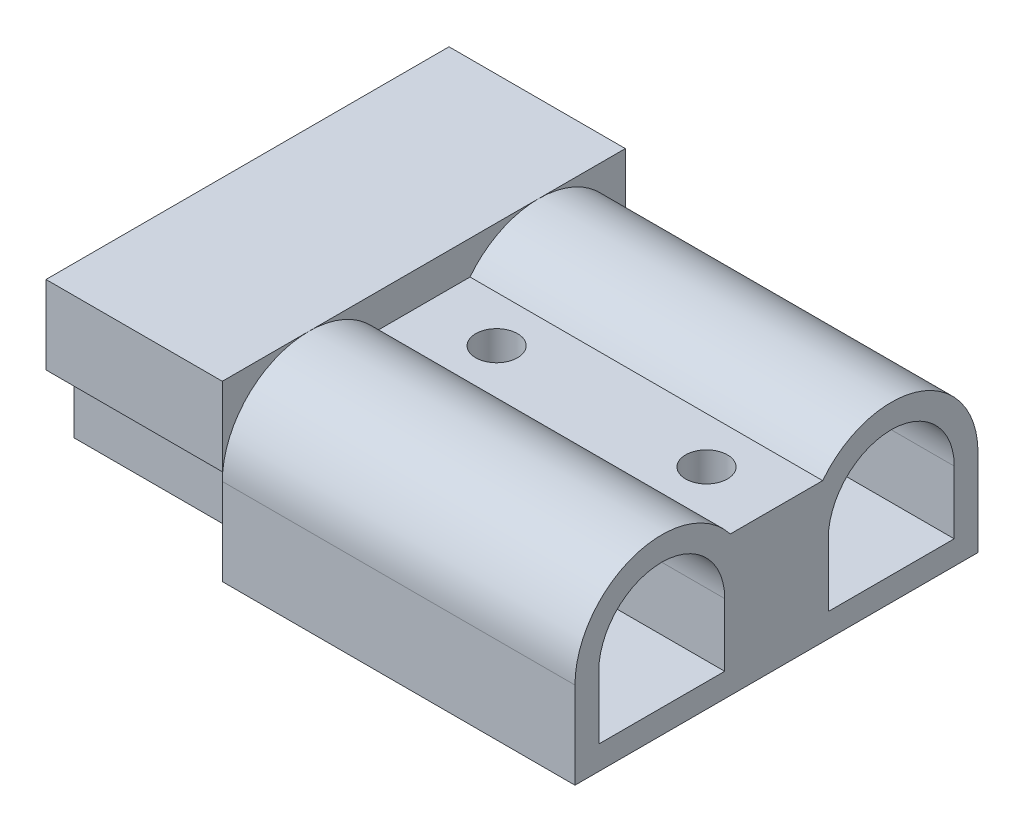
SolidWorks part; units mm, degrees
ref_plane "Front Plane" through (0, 0, 0) normal (0, 0, 1) x (1, 0, 0)
ref_plane "Top Plane" through (0, 0, 0) normal (0, 1, 0) x (1, 0, 0)
ref_plane "Right Plane" through (0, 0, 0) normal (1, 0, 0) x (0, 0, -1)
ref_plane "Plane1" through (0, 7.874, 0) normal (0, 1, 0) x (1, 0, 0)
sketch "Sketch1" plane through (0, 7.874, 0) normal (0, 1, 0) x (1, 0, 0)
  line L0 (0, -18.288) -> (0, 18.288)
  line L1 (0, 18.288) -> (-16.002, 18.288)
  line L2 (-16.002, 18.288) -> (-16.002, -18.288)
  line L3 (-16.002, -18.288) -> (0, -18.288)
extrude "Boss-Extrude1" add sketch "Sketch1" against normal blind 7.112
sketch "Sketch2" plane through (0, 0.762, 0) normal (0, -1, 0) x (1, 0, 0)
  line L0 (-16.002, -18.288) -> (-16.002, 18.288)
  line L1 (-16.002, 18.288) -> (0, 18.288)
  line L2 (0, 18.288) -> (0, -15.748)
  line L3 (0, -18.288) -> (-16.002, -18.288)
  spline S0 degree 3 poles (0, -18.288) (0, -17.4413) (0, -16.5947) (0, -15.748) knots 0 0 0 0 1 1 1 1
extrude "Boss-Extrude2" add sketch "Sketch2" along normal blind 6.604
sketch "Sketch3" plane through (0, 0, -18.288) normal (0, 0, -1) x (-1, 0, 0)
  line L0 (0, 0.762) -> (0, -5.842)
  line L1 (0, -5.842) -> (16.002, -5.842)
  line L2 (16.002, -5.842) -> (16.002, 0.762)
  line L3 (16.002, 0.762) -> (0, 0.762)
extrude "Cut-Extrude1" cut sketch "Sketch3" against normal blind 2.54
sketch "Sketch4" plane through (0, -5.842, 0) normal (0, -1, 0) x (1, 0, 0)
  line L0 (0, 15.748) -> (0, 18.288)
  line L1 (0, 18.288) -> (-16.002, 18.288)
  line L2 (-16.002, 18.288) -> (-16.002, 15.748)
  line L3 (-16.002, 15.748) -> (0, 15.748)
extrude "Cut-Extrude2" cut sketch "Sketch4" against normal blind 6.604
sketch "Sketch5" plane through (0, 0, 0) normal (1, 0, 0) x (0, 0, -1)
  line L0 (4.699, 0) -> (4.699, -5.715)
  line L1 (4.699, -5.715) -> (16.129, -5.715)
  line L2 (16.129, -5.715) -> (16.129, 0)
  line L3 (-18.288, -5.842) -> (-18.288, 0)
  line L4 (-4.1923, 4.826) -> (4.1923, 4.826)
  line L5 (18.288, 0) -> (18.288, -5.842)
  line L6 (18.288, -5.842) -> (-18.288, -5.842)
  line L7 (-16.129, 0) -> (-16.129, -5.715)
  line L8 (-16.129, -5.715) -> (-4.699, -5.715)
  line L9 (-4.699, -5.715) -> (-4.699, 0)
  arc A0 (16.129, 0) -> (4.699, 0) centre (10.414, 0) ccw
  arc A1 (-18.288, 0) -> (-4.1923, 4.826) centre (-10.414, 0) cw
  arc A2 (4.1923, 4.826) -> (18.288, 0) centre (10.414, 0) cw
  arc A3 (-4.699, 0) -> (-16.129, 0) centre (-10.414, 0) ccw
extrude "Boss-Extrude3" add sketch "Sketch5" along normal blind 32.004
sketch "Sketch6" plane through (0, -5.842, 0) normal (0, -1, 0) x (1, 0, 0)
  line L0 (32.004, -18.288) -> (0, -18.288)
  line L1 (0, -18.288) -> (0, 18.288)
  line L2 (0, 18.288) -> (32.004, 18.288)
  line L3 (32.004, 18.288) -> (32.004, -18.288)
extrude "Boss-Extrude4" add sketch "Sketch6" along normal blind 2.032
sketch "Sketch7" plane through (0, -5.842, 0) normal (0, -1, 0) x (1, 0, 0)
  line L0 (0, 1.27) -> (-16.002, 1.27)
  line L1 (-16.002, 1.27) -> (-16.002, -1.27)
  line L2 (-16.002, -1.27) -> (0, -1.27)
  line L3 (0, -1.27) -> (0, 1.27)
extrude "Cut-Extrude3" cut sketch "Sketch7" against normal blind 6.604
hole_wizard "M3.5 Clearance Hole1" positions "Sketch9" profile "Sketch8" hole size "M3.5" standard "ANSI Metric"
sketch "Sketch9" plane through (0, 4.826, 0) normal (0, 1, 0) x (1, 0, 0)
  point P0 (25.654, 0)
  point P1 (6.604, 0)
sketch "Sketch8" plane through (25.654, 4.826, 0) normal (1, 0, 0) x (0, 0, 1)
  line L0 (0, 0) -> (0, 12.7)
  line L1 (0, 12.7) -> (1.8986, 12.7)
  line L2 (1.8986, 12.7) -> (1.8986, 0)
  line L5 (1.8986, 0) -> (0, 0)
  line L11 (0, -6.35) -> (0, 107.95) construction
  dimension "Thru Hole Dia." = 3.7973
  dimension "Thru Hole Depth" = 12.7
